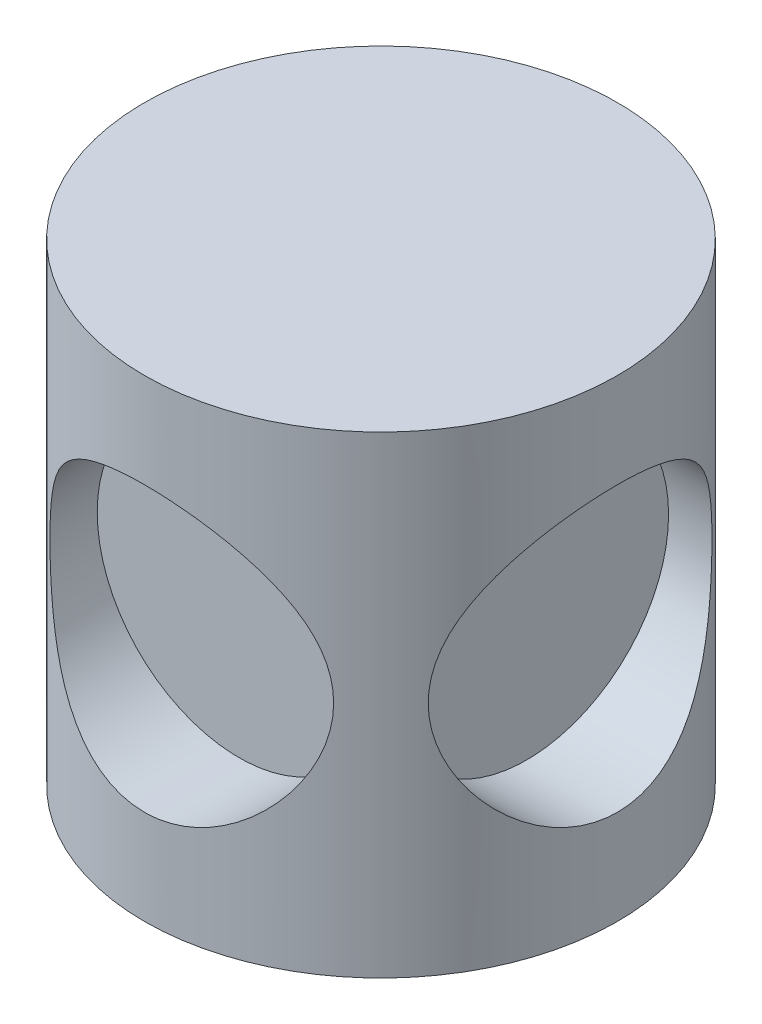
SolidWorks part; units mm, degrees
ref_plane "Front Plane" through (0, 0, 0) normal (0, 0, 1) x (1, 0, 0)
ref_plane "Top Plane" through (0, 0, 0) normal (0, 1, 0) x (1, 0, 0)
ref_plane "Right Plane" through (0, 0, 0) normal (1, 0, 0) x (0, 0, -1)
sketch "Sketch1" plane through (0, 0, 0) normal (0, 1, 0) x (1, 0, 0)
  circle A0 centre (0, 0) radius 50
  dimension "D1" = 100
extrude "Boss-Extrude1" add sketch "Sketch1" along normal blind 100
ref_plane "Plane1" through (0, 0, 50) normal (0, 0, 1) x (1, 0, 0)
sketch "Sketch2" plane through (0, 0, 50) normal (0, 0, 1) x (1, 0, 0)
  circle A0 centre (0, 50) radius 30
  dimension "D1" = 60
extrude "Cut-Extrude1" cut sketch "Sketch2" against normal blind 20
ref_plane "Plane2" through (50.8303, 0, 0) normal (1, 0, 0) x (0, 0, -1)
sketch "Sketch3" plane through (50.8303, 0, 0) normal (1, 0, 0) x (0, 0, -1)
  circle A0 centre (0, 50) radius 30
  dimension "D1" = 60
extrude "Cut-Extrude2" cut sketch "Sketch3" against normal blind 20
